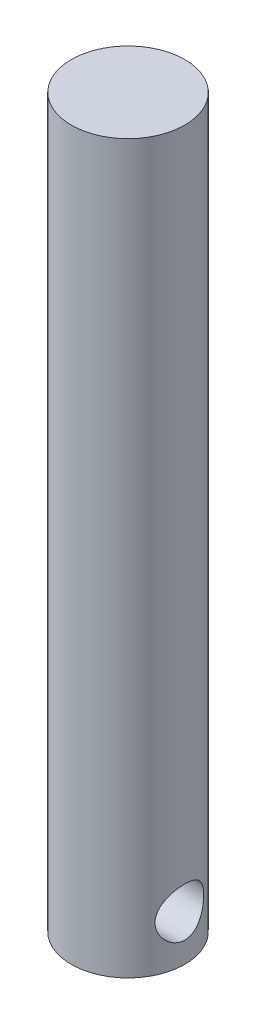
SolidWorks part; units mm, degrees
ref_plane "Front Plane" through (0, 0, 0) normal (0, 0, 1) x (1, 0, 0)
ref_plane "Top Plane" through (0, 0, 0) normal (0, 1, 0) x (1, 0, 0)
ref_plane "Right Plane" through (0, 0, 0) normal (1, 0, 0) x (0, 0, -1)
sketch "Sketch1" plane through (0, 0, 0) normal (0, 1, 0) x (1, 0, 0)
  circle A0 centre (0, 0) radius 3.9688
  dimension "D1" = 7.9375
extrude "Boss-Extrude1" add sketch "Sketch1" along normal blind 50.8
ref_plane "Plane1" through (3.9688, 0, 0) normal (1, 0, 0) x (0, 0, -1)
sketch "Sketch2" plane through (3.9688, 0, 0) normal (1, 0, 0) x (0, 0, -1)
  circle A0 centre (0, 3.175) radius 1.7
  dimension "D2" = 3.4
  dimension "D1" = 3.175
extrude "Cut-Extrude1" cut sketch "Sketch2" against normal up to next
move or copy body "Body-Move/Copy1" bodies to move or copy 103 parameters "D1"=0, "D2"=0, "D3"=0
